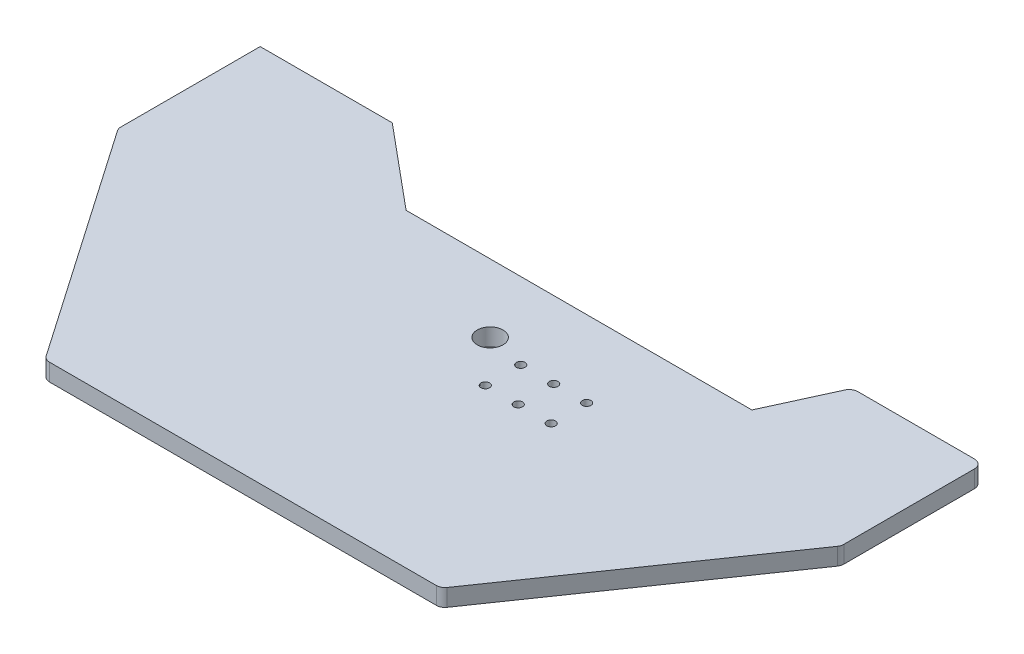
SolidWorks part; units mm, degrees
material "Oak"
ref_plane "Front Plane" through (0, 0, 0) normal (0, 0, 1) x (1, 0, 0)
ref_plane "Top Plane" through (0, 0, 0) normal (0, 1, 0) x (1, 0, 0)
ref_plane "Right Plane" through (0, 0, 0) normal (1, 0, 0) x (0, 0, -1)
sketch "Sketch1" plane through (0, 0, 0) normal (0, 1, 0) x (1, 0, 0)
  line L0 (-266.7, -139.7) -> (266.7, -139.7)
  line L1 (-266.7, -139.7) -> (-266.7, 139.7)
  line L2 (-266.7, 139.7) -> (-169.2275, 139.7)
  line L3 (-169.2275, 139.7) -> (-108.2377, 88.9)
  line L4 (-108.2377, 88.9) -> (146.939, 88.9)
  line L5 (146.939, 88.9) -> (170.18, 139.7)
  line L6 (170.18, 139.7) -> (266.7, 139.7)
  line L7 (266.7, 139.7) -> (266.7, -139.7)
  point P2 (0, -139.7)
  point P4 (266.7, 0)
  dimension "D1" = 96.52
  dimension "D2" = 533.4
  dimension "D3" = 279.4
  dimension "D4" = 50.8
  dimension "D5" = 23.241
  dimension "D6" = 97.4725
  dimension "D7" = 79.375
extrude "Boss-Extrude1" add sketch "Sketch1" along normal mid plane 12.7
sketch "Sketch2" plane through (0, 6.35, 0) normal (0, 1, 0) x (1, 0, 0)
  line L0 (-266.7, -2.0701) -> (266.7, -2.0701) construction
  line L1 (-266.7, 139.7) -> (-266.7, -139.7) construction
  line L2 (266.7, -139.7) -> (266.7, 139.7) construction
  line L3 (266.7, 139.7) -> (170.18, 139.7) construction
  line L4 (32.8422, 32.4104) -> (81.4832, 32.4104) construction
  line L5 (81.4832, 32.4104) -> (81.4832, 6.2484) construction
  line L6 (81.4832, 6.2484) -> (32.8422, 6.2484) construction
  line L7 (32.8422, 6.2484) -> (32.8422, 32.4104) construction
  line L8 (57.1627, 6.2484) -> (57.1627, 32.4104) construction
  circle A0 centre (81.4832, 6.2484) radius 3.175
  circle A1 centre (81.4832, 32.4104) radius 3.175
  circle A2 centre (57.1627, 32.4104) radius 3.175
  circle A3 centre (32.8422, 32.4104) radius 3.175
  circle A4 centre (32.8422, 6.2484) radius 3.175
  circle A5 centre (57.1627, 6.2484) radius 3.175
  dimension "D2" = 6.35
  dimension "D1" = 141.7701
  dimension "D3" = 48.641
  dimension "D4" = 185.2168
  dimension "D5" = 8.3185
  dimension "D6" = 26.162
extrude "Cut-Extrude1" cut sketch "Sketch2" against normal through all
sketch "Sketch3" plane through (0, 6.35, 0) normal (0, 1, 0) x (1, 0, 0)
  line L0 (-266.7, 34.925) -> (-146.05, -139.7)
  line L1 (-266.7, 139.7) -> (-266.7, -139.7) construction
  line L2 (-266.7, -139.7) -> (266.7, -139.7) construction
  line L3 (-146.05, -139.7) -> (-266.7, -139.7)
  line L4 (-266.7, -139.7) -> (-266.7, 34.925)
  dimension "D1" = 174.625
  dimension "D2" = 120.65
extrude "Cut-Extrude2" cut sketch "Sketch3" against normal through all
mirror "Mirror1" about plane through (0, 0, 0) normal (1, 0, 0) of "Cut-Extrude2"
fillet "Fillet1" radius 6.35 6 edges at (170.18, 0, -139.7) (266.7, 0, -139.7) (266.7, 0, -34.925) (146.05, 0, 139.7) (-146.05, 0, 139.7) (-266.7, 0, -34.925)
sketch "Sketch4" plane through (0, 6.35, 0) normal (0, 1, 0) x (1, 0, 0)
  line L1 (28.1735, 25.05) -> (22.1735, 25.05) construction
  line L2 (28.1735, 37.55) -> (28.1735, 0.55) construction
  circle A0 centre (3.9997, 38.6754) radius 9.525
  point P2 (0, 0)
  dimension "D1" = 19.05
  dimension "D2" = 13.6254
  dimension "D3" = 24.1738
extrude "Cut-Extrude3" cut sketch "Sketch4" against normal through all
